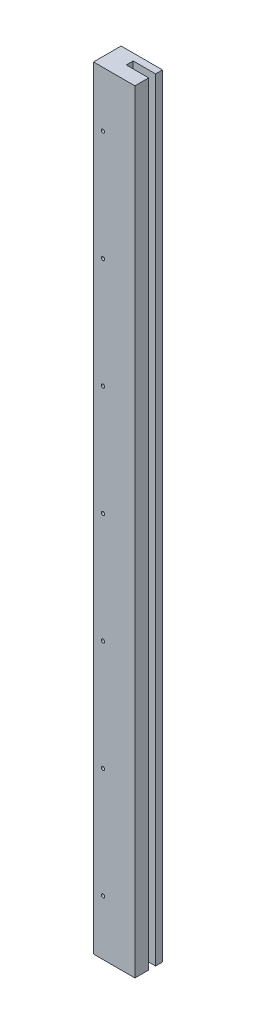
SolidWorks part; units mm, degrees
ref_plane "Front Plane" through (0, 0, 0) normal (0, 0, 1) x (1, 0, 0)
ref_plane "Top Plane" through (0, 0, 0) normal (0, 1, 0) x (1, 0, 0)
ref_plane "Right Plane" through (0, 0, 0) normal (1, 0, 0) x (0, 0, -1)
sketch "Sketch2" plane through (0, 0, 0) normal (0, 1, 0) x (1, 0, 0)
  line L0 (-438.15, -304.8) -> (-438.15, -292.1)
  line L1 (-476.25, -304.8) -> (476.25, -304.8) construction
  line L2 (-438.15, -292.1) -> (-458.7875, -292.1)
  line L3 (-458.7875, -292.1) -> (-458.7875, -285.75)
  line L4 (-458.7875, -285.75) -> (-438.15, -285.75)
  line L5 (-438.15, -285.75) -> (-438.15, -279.4)
  line L6 (-438.15, -279.4) -> (-476.25, -279.4)
  line L7 (-476.25, 298.45) -> (-476.25, -304.8) construction
  line L8 (-476.25, -279.4) -> (-476.25, -304.8)
  line L9 (-476.25, -304.8) -> (-438.15, -304.8)
  line L10 (-457.2, -292.1) -> (-457.2, -285.75) construction
  line L11 (-457.2, -288.925) -> (-458.7875, -288.925) construction
  line L12 (-476.25, -279.4) -> (476.25, -279.4) construction
  dimension "D1" = 6.35
  dimension "D2" = 25.4
  dimension "D3" = 38.1
  dimension "D4" = 1.5875
extrude "Boss-Extrude1" add sketch "Sketch2" along normal up to surface (711.2 mm away)
sketch "Sketch3" plane through (-458.7875, 0, 0) normal (1, 0, 0) x (0, 0, -1)
  line L0 (-288.925, 711.2) -> (-288.925, -49288.8) construction
  line L4 (-285.75, 711.2) -> (-292.1, 711.2)
  line L5 (-292.1, 711.2) -> (-292.1, 0)
  line L6 (-292.1, 0) -> (-285.75, 0)
  line L7 (-285.75, 0) -> (-285.75, 711.2)
  line L8 (-285.75, 711.2) -> (-292.1, 711.2) construction
  line L9 (-292.1, 711.2) -> (-292.1, 0) construction
  line L10 (-292.1, 0) -> (-285.75, 0) construction
  line L11 (-285.75, 0) -> (-285.75, 711.2) construction
  circle A0 centre (-288.925, 609.6) radius 3.175
  point P8 (-288.925, 711.2)
  dimension "D2" = 6.35
  dimension "D3" = 101.6
  dimension "D1" = 0
extrude "Sash Adjustment Holes Cut" cut sketch "Sketch3" against normal through all
pattern_linear "LPattern1" count 6 spacing 101.6 along (0, -1, 0) of "Sash Adjustment Holes Cut"
sketch "Sketch4" plane through (0, 0, 304.8) normal (0, 0, 1) x (1, 0, 0)
  line L0 (-467.5188, 0) -> (-467.5188, 711.2) construction
  line L1 (-476.25, 0) -> (-438.15, 0) construction
  line L2 (-476.25, 711.2) -> (-438.15, 711.2) construction
  line L3 (-458.7875, 0) -> (-476.25, 0) construction
  line L10 (-438.15, 711.2) -> (-458.7875, 711.2)
  line L11 (-458.7875, 711.2) -> (-458.7875, 609.6)
  line L12 (-458.7875, 609.6) -> (-458.7875, 508)
  line L13 (-458.7875, 508) -> (-458.7875, 406.4)
  line L14 (-458.7875, 406.4) -> (-458.7875, 304.8)
  line L15 (-458.7875, 304.8) -> (-458.7875, 203.2)
  line L16 (-458.7875, 203.2) -> (-458.7875, 101.6)
  line L17 (-458.7875, 101.6) -> (-458.7875, 0)
  line L18 (-458.7875, 0) -> (-438.15, 0)
  line L19 (-438.15, 0) -> (-438.15, 711.2)
  line L20 (-438.15, 711.2) -> (-458.7875, 711.2) construction
  line L21 (-458.7875, 711.2) -> (-458.7875, 609.6) construction
  line L22 (-458.7875, 609.6) -> (-458.7875, 508) construction
  line L23 (-458.7875, 508) -> (-458.7875, 406.4) construction
  line L24 (-458.7875, 406.4) -> (-458.7875, 304.8) construction
  line L25 (-458.7875, 304.8) -> (-458.7875, 203.2) construction
  line L26 (-458.7875, 203.2) -> (-458.7875, 101.6) construction
  line L27 (-458.7875, 101.6) -> (-458.7875, 0) construction
  line L28 (-458.7875, 0) -> (-438.15, 0) construction
  line L29 (-438.15, 0) -> (-438.15, 711.2) construction
  circle A0 centre (-467.5188, 50.8) radius 1.5875
  dimension "D2" = 3.175
  dimension "D3" = 50.8
  dimension "D1" = 0
extrude "Mounting Screw Holes Cut" cut sketch "Sketch4" against normal through all
pattern_linear "LPattern2" count 7 spacing 101.6 along (0, 1, 0) of "Mounting Screw Holes Cut"
equation "\"D1@Boss-Extrude1\"=\"inner_height\""
equation "\"inner_height\"= 30in"
equation "\"D3@LPattern1\"=\"D3@Sketch3\""
